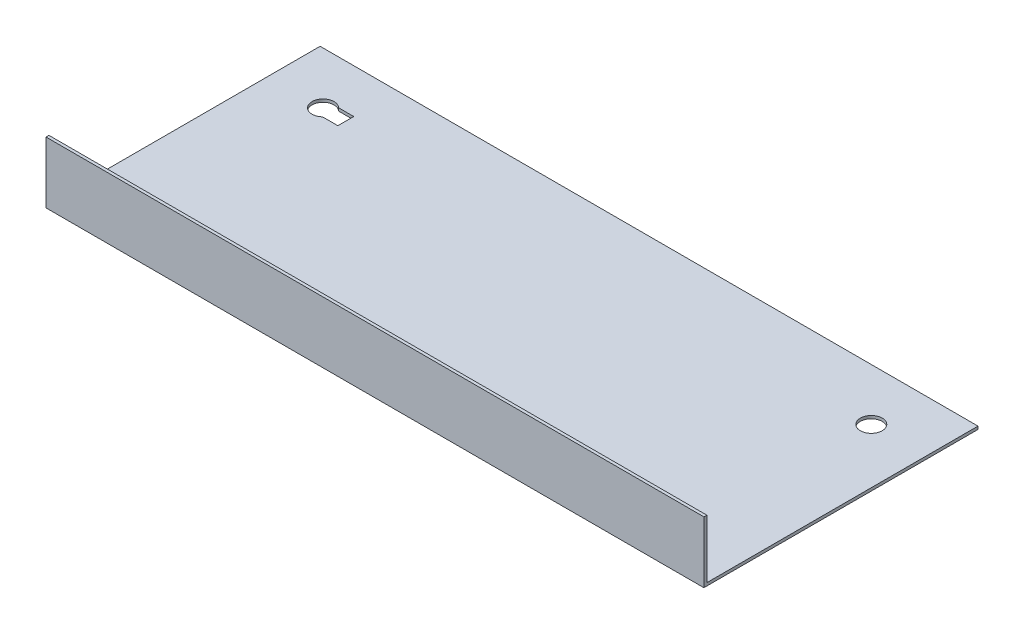
SolidWorks part; units mm, degrees
ref_plane "Front Plane" through (0, 0, 0) normal (0, 0, 1) x (1, 0, 0)
ref_plane "Top Plane" through (0, 0, 0) normal (0, 1, 0) x (1, 0, 0)
ref_plane "Right Plane" through (0, 0, 0) normal (1, 0, 0) x (0, 0, -1)
sketch "Sketch1" plane through (0, 0, 0) normal (0, 1, 0) x (1, 0, 0)
  line L1 (-450, -187.5) -> (450, -187.5)
  line L2 (-450, -187.5) -> (-450, 187.5)
  line L3 (-450, 187.5) -> (450, 187.5)
  line L4 (450, -187.5) -> (450, 187.5)
  line L5 (-450, -187.5) -> (450, 187.5) construction
  line L6 (-450, 187.5) -> (450, -187.5) construction
  point P0 (0, 0)
  dimension "D1" = 900
  dimension "D2" = 375
extrude "Boss-Extrude1" add sketch "Sketch1" along normal blind 4
sketch "Sketch2" plane through (0, 4, 0) normal (0, 1, 0) x (1, 0, 0)
  line L0 (450, -187.5) -> (450, 187.5) construction
  line L1 (-450, -187.5) -> (450, -187.5)
  line L2 (-450, -187.5) -> (-450, -183.5)
  line L3 (-450, -183.5) -> (450, -183.5)
  line L4 (450, -187.5) -> (450, -183.5)
  dimension "D1" = 4
extrude "Boss-Extrude2" add sketch "Sketch2" along normal blind 80
sketch "Sketch3" plane through (0, 4, 0) normal (0, 1, 0) x (1, 0, 0)
  line L0 (0, -183.5) -> (0, 116.5) construction
  line L1 (450, -183.5) -> (-450, -183.5) construction
  line L2 (375, 116.5) -> (-375, 116.5) construction
  circle A0 centre (375, 116.5) radius 15
  circle A1 centre (-375, 116.5) radius 15
  point P8 (0, 116.5)
  point P14 (-339.4332, 116.5)
  dimension "D4" = 30
  dimension "D1" = 300
  dimension "D2" = 750
  dimension "D3" = 0
extrude "Cut-Extrude1" cut sketch "Sketch3" against normal blind 80
ref_plane "Plane1" through (0, 30, 0) normal (0, -1, 0) x (-1, 0, 0)
sketch "Sketch6" plane through (0, 30, 0) normal (0, -1, 0) x (-1, 0, 0)
  line L0 (375.4767, 116.2746) -> (375.4767, 127.2863)
  line L1 (375.4767, 127.2863) -> (343.7473, 127.2863)
  line L2 (343.7473, 127.2863) -> (343.7473, 105.5289)
  line L3 (343.7473, 105.5289) -> (375.4767, 105.5289)
  line L4 (375.4767, 105.5289) -> (375.4767, 116.2746)
  point P2 (375.4767, 127.2863)
extrude "Cut-Extrude2" cut sketch "Sketch6" along normal blind 48 contours L0 L1 L2 L3 L4
